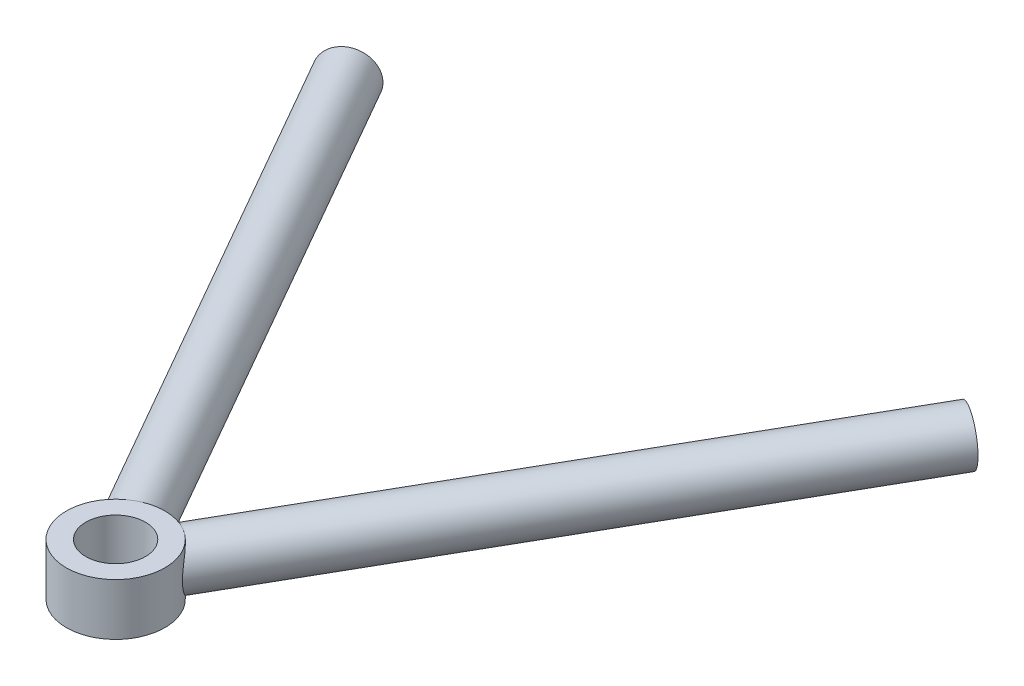
SolidWorks part; units mm, degrees
material "AISI 4130 Steel, annealed at 865C"
ref_plane "Front Plane" through (0, 0, 0) normal (0, 0, 1) x (1, 0, 0)
ref_plane "Top Plane" through (0, 0, 0) normal (0, 1, 0) x (1, 0, 0)
ref_plane "Right Plane" through (0, 0, 0) normal (1, 0, 0) x (0, 0, -1)
sketch "Sketch1" plane through (0, 0, 0) normal (0, 1, 0) x (1, 0, 0)
  circle A0 centre (0, 0) radius 11.5062
  circle A1 centre (0, 0) radius 19.0062
  dimension "D3" = 23.0124
  dimension "D1" = 38.0124
extrude "Boss-Extrude1" add sketch "Sketch1" along normal mid plane 20
sketch "Sketch3" plane through (0, 0, 0) normal (0, 1, 0) x (1, 0, 0)
  line L0 (-19.0062, 0) -> (19.0062, 0) construction
  line L1 (0, 0) -> (-135.5, 236.7546) construction
  line L2 (0, 0) -> (119.7431, 209.223) construction
  line L3 (-9.4408, 16.4956) -> (-135.5, 236.7546) construction
  line L4 (9.4408, 16.4956) -> (119.7431, 209.223) construction
  line L6 (119.7431, 209.223) -> (142.373, 196.2714) construction
  line L7 (-119.7431, 209.223) -> (-148.082, 193.004) construction
  line L8 (0, 0) -> (135.5, 236.7546) construction
  line L9 (-135.5, 236.7546) -> (135.5, 236.7546) construction
  circle A0 centre (0, 0) radius 19.0062 construction
  circle A1 centre (0, 0) radius 19.0062 construction
  dimension "D1" = 60.217
  dimension "D2" = 60.217
  dimension "D3" = 272.7874
  dimension "D5" = 31.7217
  dimension "D4" = 272.7874
  dimension "D6" = 31.7217
ref_plane "tube1plane" through (119.7431, 0, -209.223) normal (0.4967, 0, -0.8679) x (0.8679, 0, 0.4967)
ref_plane "tube2plane" through (-119.7431, 0, -209.223) normal (-0.4967, 0, -0.8679) x (-0.8679, 0, 0.4967)
sketch "Sketch5" plane through (119.7431, 0, -209.223) normal (0.4967, 0, -0.8679) x (0.8679, 0, 0.4967)
  circle A0 centre (0, 0) radius 10
  circle A1 centre (0, 0) radius 7
  dimension "D1" = 20
  dimension "D2" = 14
extrude "Boss-Extrude2" add sketch "Sketch5" against normal up to next
sketch "Sketch6" plane through (-119.7431, 0, -209.223) normal (-0.4967, 0, -0.8679) x (-0.8679, 0, 0.4967)
  circle A0 centre (0, 0) radius 10
  circle A1 centre (0, 0) radius 7
  dimension "D1" = 20
  dimension "D2" = 14
extrude "Boss-Extrude3" add sketch "Sketch6" against normal up to surface (224.9029 mm away)
equation "\"CA_ID\"= 14"
equation "\"D2@Sketch5\"=\"CA_ID\""
equation "\"D2@Sketch6\"=\"CA_ID\""
equation "\"tube_end_to_ball_center\" = 31.721675mm"
equation "\"D6@Sketch3\"=\"tube_end_to_ball_center\""
equation "\"D5@Sketch3\"=\"tube_end_to_ball_center\""
